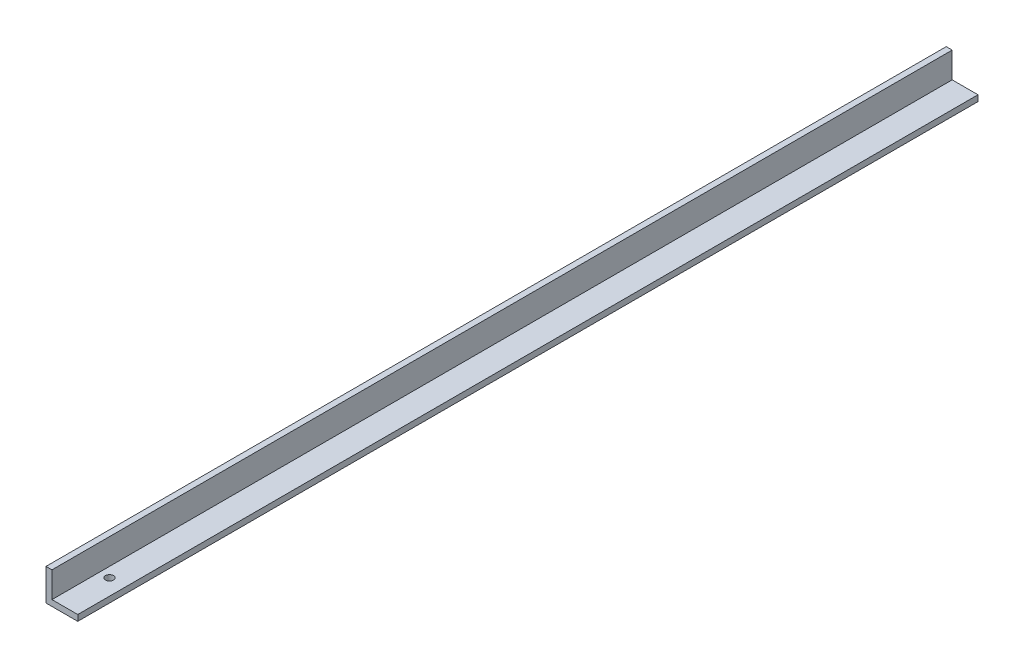
SolidWorks part; units mm, degrees
ref_plane "Front Plane" through (0, 0, 0) normal (0, 0, 1) x (1, 0, 0)
ref_plane "Top Plane" through (0, 0, 0) normal (0, 1, 0) x (1, 0, 0)
ref_plane "Right Plane" through (0, 0, 0) normal (1, 0, 0) x (0, 0, -1)
sketch "Sketch1" plane through (0, 0, 0) normal (0, 0, 1) x (1, 0, 0)
  line L0 (0, 0) -> (0, -20.6375)
  line L1 (0, -20.6375) -> (20.6375, -20.6375)
  line L2 (-4.7625, 0) -> (-4.7625, -25.4)
  line L3 (-4.7625, -25.4) -> (20.6375, -25.4)
  line L4 (-4.7625, 0) -> (0, 0)
  line L5 (20.6375, -20.6375) -> (20.6375, -25.4)
  dimension "D2" = 4.7625
  dimension "D3" = 25.4
  dimension "D4" = 25.4
  dimension "D1" = 4.7625
extrude "Boss-Extrude1" add sketch "Sketch1" along normal blind 720.09
sketch "Sketch2" plane through (0, -20.6375, 0) normal (0, 1, 0) x (1, 0, 0)
  line L0 (20.6375, -720.09) -> (0, -720.09) construction
  line L1 (20.6375, -720.09) -> (20.6375, 0) construction
  circle A0 centre (7.9375, -681.99) radius 3.175
  dimension "D1" = 6.35
  dimension "D2" = 38.1
  dimension "D3" = 12.7
extrude "Cut-Extrude1" cut sketch "Sketch2" against normal up to next
